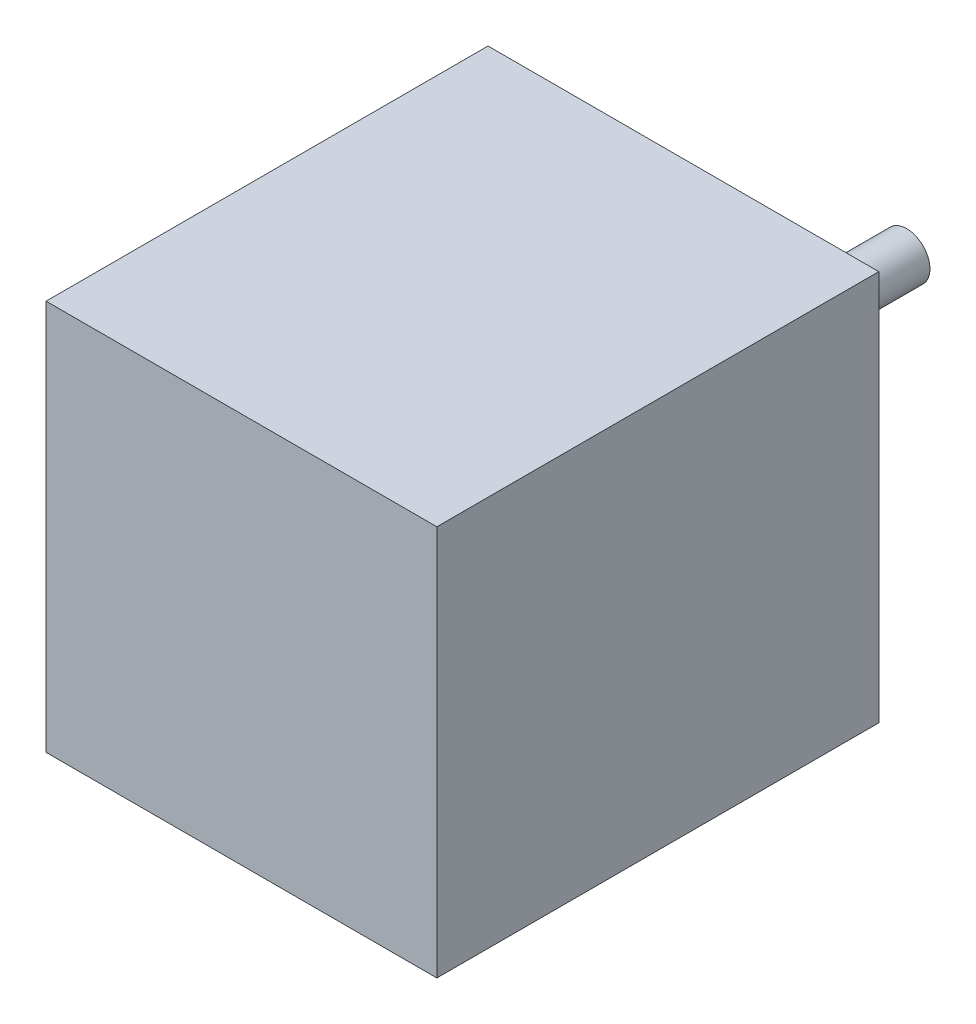
SolidWorks part; units mm, degrees
ref_plane "前视基准面" through (0, 0, 0) normal (0, 0, 1) x (1, 0, 0)
ref_plane "上视基准面" through (0, 0, 0) normal (0, 1, 0) x (1, 0, 0)
ref_plane "右视基准面" through (0, 0, 0) normal (1, 0, 0) x (0, 0, -1)
sketch "草图1" plane through (0, 0, 0) normal (0, 0, 1) x (1, 0, 0)
  line L1 (0, 0) -> (-42, 0)
  line L2 (0, 0) -> (0, 42)
  line L3 (0, 42) -> (-42, 42)
  line L4 (-42, 0) -> (-42, 42)
  dimension "D1" = 42
  dimension "D2" = 42
extrude "凸台-拉伸1" add sketch "草图1" along normal blind 47.5
sketch "草图3" plane through (0, 0, 0) normal (0, 0, -1) x (-1, 0, 0)
  line L0 (0, 42) -> (42, 42) construction
  line L1 (0, 0) -> (0, 42) construction
  circle A0 centre (21, 21) radius 11
  dimension "D3" = 22
  dimension "D1" = 21
  dimension "D2" = 21
extrude "凸台-拉伸2" add sketch "草图3" along normal blind 2
sketch "草图4" plane through (0, 0, -2) normal (0, 0, -1) x (-1, 0, 0)
  circle A0 centre (21, 21) radius 2.5
  dimension "D1" = 5
extrude "凸台-拉伸3" add sketch "草图4" along normal blind 22
sketch "草图5" plane through (0, 0, 0) normal (0, 0, -1) x (-1, 0, 0)
  line L0 (0, 0) -> (5.5, 0) construction
  line L1 (42, 0) -> (0, 0) construction
  line L2 (5.5, 0) -> (5.5, 5.5) construction
  line L3 (5.5, 5.5) -> (36.5, 5.5) construction
  line L4 (36.5, 5.5) -> (36.5, 36.5) construction
  line L5 (36.5, 36.5) -> (5.5, 36.5) construction
  circle A0 centre (5.5, 5.5) radius 1.5
  circle A1 centre (36.5, 5.5) radius 1.5
  circle A2 centre (36.5, 36.5) radius 1.5
  circle A3 centre (5.5, 36.5) radius 1.5
  dimension "D6" = 3
  dimension "D7" = 3
  dimension "D8" = 3
  dimension "D9" = 3
  dimension "D1" = 5.5
  dimension "D2" = 5.5
  dimension "D3" = 31
  dimension "D4" = 31
  dimension "D5" = 31
extrude "切除-拉伸1" cut sketch "草图5" against normal blind 8
